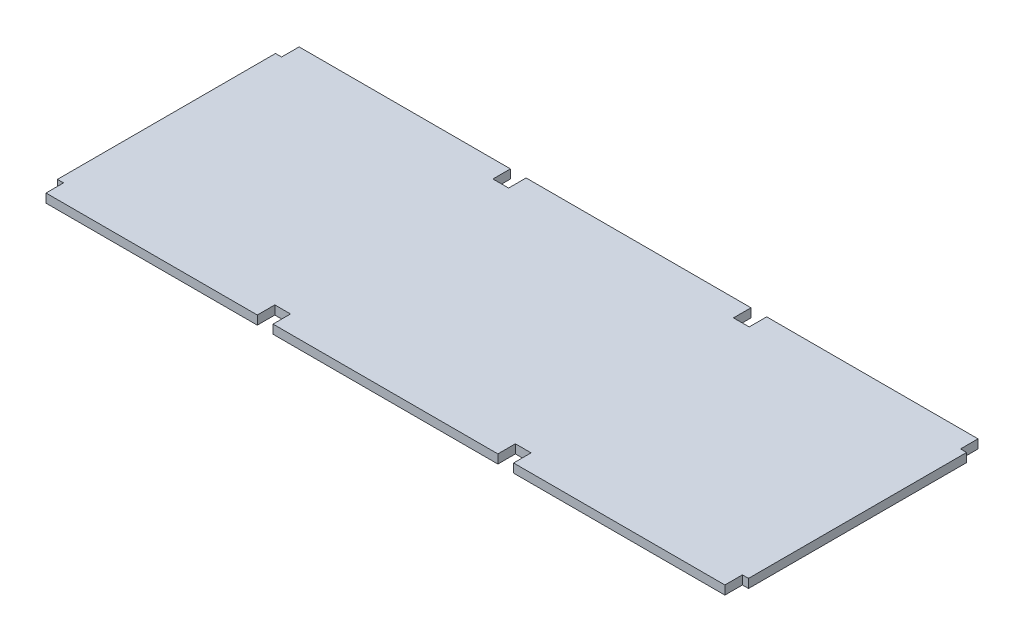
SolidWorks part; units mm, degrees
ref_plane "Front Plane" through (0, 0, 0) normal (0, 0, 1) x (1, 0, 0)
ref_plane "Top Plane" through (0, 0, 0) normal (0, 1, 0) x (1, 0, 0)
ref_plane "Right Plane" through (0, 0, 0) normal (1, 0, 0) x (0, 0, -1)
sketch "Sketch1" plane through (0, 0, 0) normal (0, 1, 0) x (1, 0, 0)
  line L0 (0, 0) -> (0, 96.5)
  line L1 (0, 96.5) -> (2.7, 96.5)
  line L2 (2.7, 96.5) -> (2.7, 104.25)
  line L3 (2.7, 104.25) -> (96.2, 104.25)
  line L4 (96.2, 104.25) -> (96.2, 96.5)
  line L5 (96.2, 96.5) -> (103.15, 96.5)
  line L6 (103.15, 96.5) -> (103.15, 104.25)
  line L7 (103.15, 104.25) -> (202.65, 104.25)
  line L8 (202.65, 104.25) -> (202.65, 96.5)
  line L9 (202.65, 96.5) -> (209.6, 96.5)
  line L10 (209.6, 96.5) -> (209.6, 104.25)
  line L11 (209.6, 104.25) -> (303.1, 104.25)
  line L12 (303.1, 104.25) -> (303.1, 96.5)
  line L13 (303.1, 96.5) -> (305.8, 96.5)
  line L14 (305.8, 96.5) -> (305.8, 0)
  line L15 (305.8, 0) -> (303.1, 0)
  line L16 (303.1, 0) -> (303.1, -7.75)
  line L17 (303.1, -7.75) -> (209.6, -7.75)
  line L18 (209.6, -7.75) -> (209.6, 0)
  line L19 (209.6, 0) -> (202.65, 0)
  line L20 (202.65, 0) -> (202.65, -7.75)
  line L21 (202.65, -7.75) -> (103.15, -7.75)
  line L22 (103.15, -7.75) -> (103.15, 0)
  line L23 (103.15, 0) -> (96.2, 0)
  line L24 (96.2, 0) -> (96.2, -7.75)
  line L25 (96.2, -7.75) -> (2.7, -7.75)
  line L26 (2.7, -7.75) -> (2.7, 0)
  line L27 (2.7, 0) -> (0, 0)
  dimension "D1" = 112
  dimension "D2" = 305.8
  dimension "D3" = 99.5
  dimension "D4" = 93.5
  dimension "D5" = 96.5
  dimension "D6" = 2.7
  dimension "D7" = 93.5
extrude "Boss-Extrude1" add sketch "Sketch1" along normal blind 3.9
